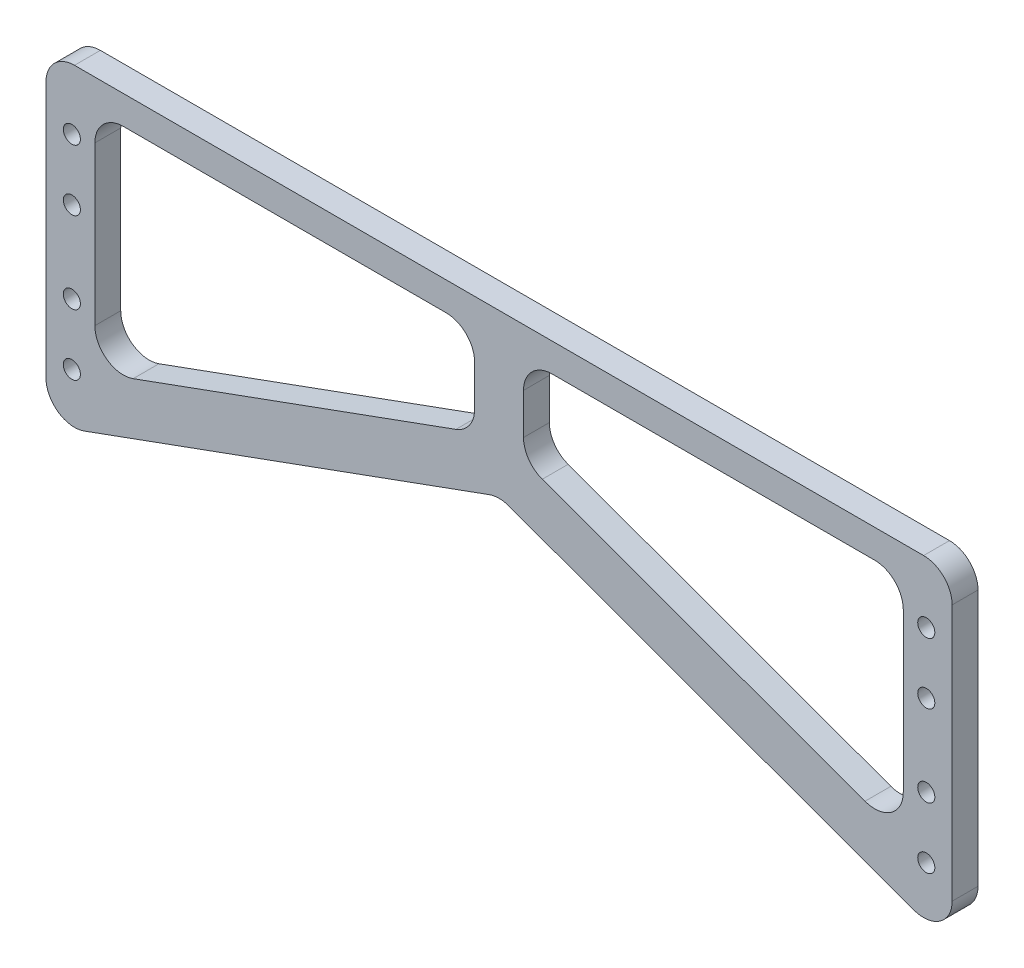
SolidWorks part; units mm, degrees
ref_plane "Front Plane" through (0, 0, 0) normal (0, 0, 1) x (1, 0, 0)
ref_plane "Top Plane" through (0, 0, 0) normal (0, 1, 0) x (1, 0, 0)
ref_plane "Right Plane" through (0, 0, 0) normal (1, 0, 0) x (0, 0, -1)
sketch "Sketch1" plane through (0, 0, 0) normal (0, 0, 1) x (1, 0, 0)
  line L1 (-111.25, -40) -> (111.25, -40)
  line L2 (-111.25, -40) -> (-111.25, 40)
  line L3 (-111.25, 40) -> (111.25, 40)
  line L4 (111.25, -40) -> (111.25, 40)
  line L5 (-111.25, -40) -> (111.25, 40) construction
  line L6 (-111.25, 40) -> (111.25, -40) construction
  point P0 (0, 0)
  dimension "D1" = 222.5
  dimension "D2" = 80
extrude "Boss-Extrude1" add sketch "Sketch1" along normal blind 6.35
sketch "Sketch2" plane through (0, 0, 6.35) normal (0, 0, 1) x (1, 0, 0)
  line L0 (111.25, -40) -> (0, 0.4917)
  line L1 (0, 0.4917) -> (-111.25, -40)
  line L2 (-111.25, -40) -> (111.25, -40)
  line L3 (0, 40) -> (0, -40) construction
  line L4 (111.25, 40) -> (-111.25, 40) construction
  dimension "D1" = 20
extrude "Cut-Extrude1" cut sketch "Sketch2" against normal through all
sketch "Sketch3" plane through (0, 0, 6.35) normal (0, 0, 1) x (1, 0, 0)
  line L0 (-99.25, 33) -> (-99.25, -22.8622)
  line L1 (-99.25, -22.8622) -> (-6, 11.078)
  line L2 (-6, 11.078) -> (-6, 33)
  line L3 (-6, 33) -> (-99.25, 33)
  line L4 (0, 0.4917) -> (0, 56.2405) construction
  line L5 (111.25, -40) -> (111.25, 40) construction
  line L7 (111.25, 40) -> (-111.25, 40) construction
  line L8 (-111.25, 40) -> (-111.25, -40) construction
  line L9 (0, 0.4917) -> (-111.25, -40) construction
  dimension "D1" = 12
  dimension "D2" = 12
  dimension "D3" = 7
  dimension "D4" = 12
extrude "Cut-Extrude2" cut sketch "Sketch3" against normal through all
hole_wizard "M5x0.8 Tapped Hole1" positions "Sketch5" profile "Sketch4" tap size "M5x0.8" standard "ANSI Metric"
sketch "Sketch5" plane through (0, 0, 0) normal (0, 0, -1) x (-1, 0, 0)
  line L0 (104.9, 40) -> (104.9, -49.7544) construction
  line L1 (-111.25, 40) -> (111.25, 40) construction
  line L6 (111.25, 40) -> (111.25, -40) construction
  point P23 (104.9, -25)
  point P25 (104.9, -10)
  point P27 (104.9, 25)
  point P29 (104.9, 10)
  dimension "D1" = 6.35
  dimension "D2" = 15
  dimension "D3" = 15
  dimension "D4" = 15
  dimension "D5" = 15
sketch "Sketch4" plane through (-104.9, -25, 0) normal (1, 0, 0) x (0, 1, 0)
  line L0 (0, 0) -> (0, 13.6618)
  line L1 (0, 13.6618) -> (2.1, 12.4)
  line L2 (2.1, 12.4) -> (2.1, 0)
  line L5 (2.1, 0) -> (0, 0)
  line L10 (0, 13.6618) -> (-2.1, 12.4) construction
  line L11 (0, -6.35) -> (0, 107.95) construction
  dimension "Tap Drill Dia." = 4.2
  dimension "Tap Drill Depth" = 12.4
  dimension "Drill Angle" = 118
cosmetic thread "Hole Thread1" parameters "D1"=6.35, "D2"=5
cosmetic thread "Hole Thread2" parameters "D1"=6.35, "D2"=5
cosmetic thread "Hole Thread3" parameters "D1"=6.35, "D2"=5
cosmetic thread "Hole Thread4" parameters "D1"=6.35, "D2"=5
mirror "Mirror1" about plane through (0, 0, 0) normal (1, 0, 0) of "M5x0.8 Tapped Hole1", "Cut-Extrude2"
fillet "Fillet1" radius 7 13 edges at (6, 11.078, 3.175) (99.25, -22.8622, 3.175) (-6, 11.078, 3.175) (-6, 33, 3.175) (99.25, 33, 3.175) (6, 33, 3.175) (-99.25, 33, 3.175) (111.25, 40, 3.175) (111.25, -40, 3.175) (0, 0.4917, 3.175) (-111.25, -40, 3.175) (-111.25, 40, 3.175) (-99.25, -22.8622, 3.175)
